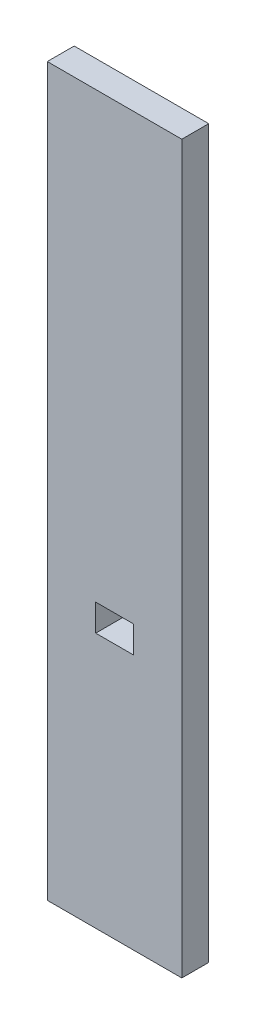
SolidWorks part; units mm, degrees
ref_plane "Front Plane" through (0, 0, 0) normal (0, 0, 1) x (1, 0, 0)
ref_plane "Top Plane" through (0, 0, 0) normal (0, 1, 0) x (1, 0, 0)
ref_plane "Right Plane" through (0, 0, 0) normal (1, 0, 0) x (0, 0, -1)
sketch "Sketch1" plane through (0, 0, 0) normal (0, 0, 1) x (1, 0, 0)
  line L0 (-25, 0) -> (25, 0) construction
  line L1 (-25, 135) -> (25, 135)
  line L2 (-25, 135) -> (-25, -135)
  line L3 (-25, -135) -> (25, -135)
  line L4 (25, 135) -> (25, -135)
  point P6 (0, 0)
  dimension "D1" = 50
  dimension "D2" = 270
extrude "Boss-Extrude1" add sketch "Sketch1" along normal blind 10
sketch "Sketch2" plane through (0, 0, 10) normal (0, 0, 1) x (1, 0, 0)
  line L0 (0, 135) -> (0, -135) construction
  line L1 (25, 135) -> (-25, 135) construction
  line L2 (-25, -135) -> (25, -135) construction
  line L4 (-7, -30) -> (7, -30)
  line L5 (-7, -30) -> (-7, -40)
  line L6 (-7, -40) -> (7, -40)
  line L7 (7, -30) -> (7, -40)
  point P10 (0, -40)
  point P11 (-7, -35)
  dimension "D1" = 14
  dimension "D2" = 10
  dimension "D3" = 100
  dimension "D4" = 165
extrude "Cut-Extrude1" cut sketch "Sketch2" against normal through all
